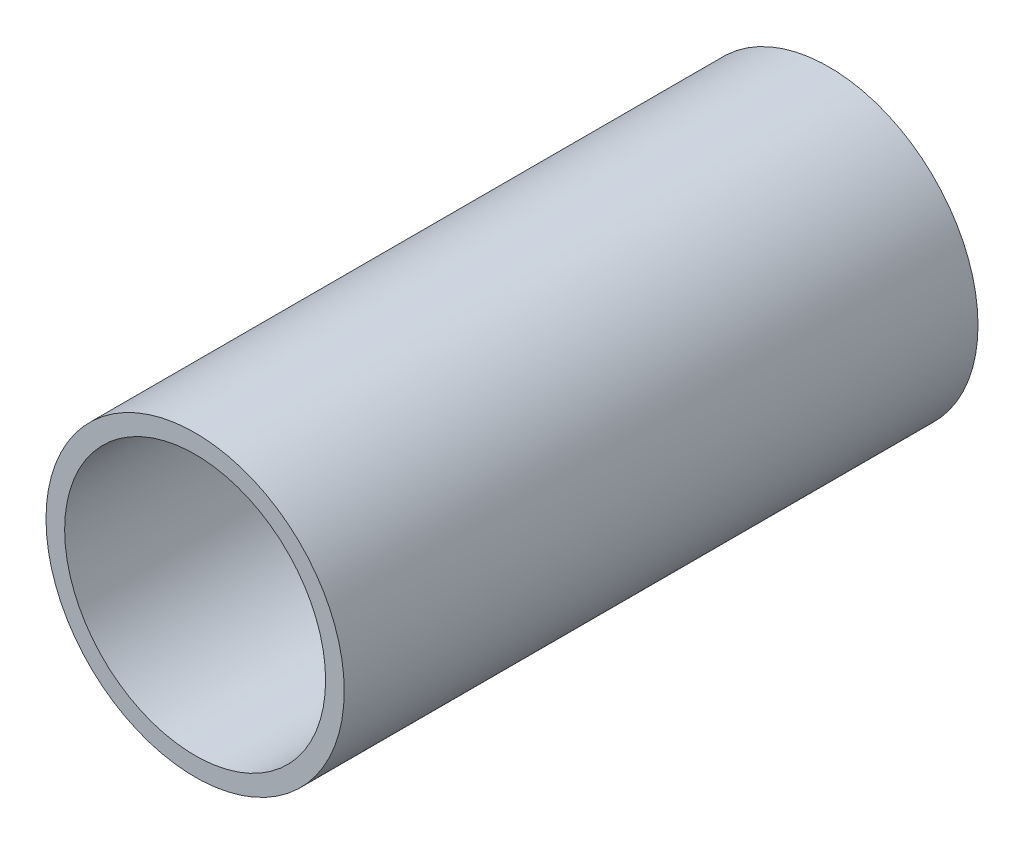
SolidWorks part; units mm, degrees
ref_plane "Plano frontal" through (0, 0, 0) normal (0, 0, 1) x (1, 0, 0)
ref_plane "Plano superior" through (0, 0, 0) normal (0, 1, 0) x (1, 0, 0)
ref_plane "Plano direito" through (0, 0, 0) normal (1, 0, 0) x (0, 0, -1)
sketch "Esboço1" plane through (0, 0, 0) normal (0, 0, 1) x (1, 0, 0)
  circle A0 centre (0, 0) radius 4
extrude "Ressalto-extrusão1" add sketch "Esboço1" along normal blind 17
ref_plane "Plano1" through (0, 0, 17) normal (0, 0, 1) x (1, 0, 0)
sketch "Esboço2" plane through (0, 0, 17) normal (0, 0, 1) x (1, 0, 0)
  circle A0 centre (0, 0) radius 3.5
extrude "Corte-extrusão1" cut sketch "Esboço2" against normal blind 15
